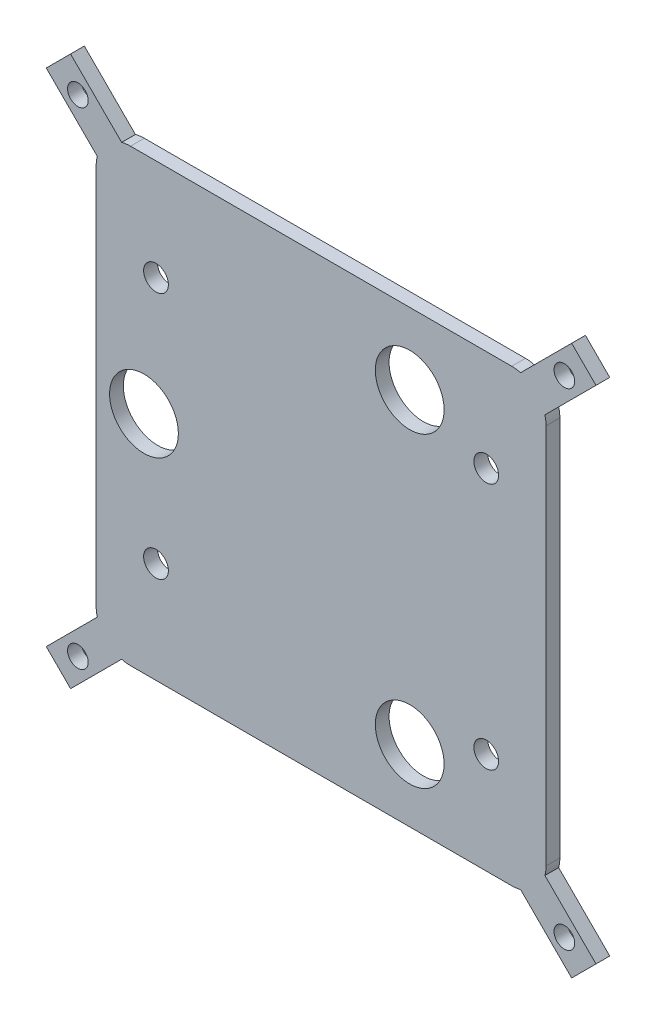
SolidWorks part; units mm, degrees
ref_plane "前视基准面" through (0, 0, 0) normal (0, 0, 1) x (1, 0, 0)
ref_plane "上视基准面" through (0, 0, 0) normal (0, 1, 0) x (1, 0, 0)
ref_plane "右视基准面" through (0, 0, 0) normal (1, 0, 0) x (0, 0, -1)
other "Configuration Table"
sketch "草图1" plane through (0, 0, 0) normal (0, 0, 1) x (1, 0, 0)
  line L0 (-24, 18) -> (24, 18) construction
  line L1 (24, 18) -> (24, -18) construction
  line L2 (24, -18) -> (-24, -18) construction
  line L3 (-24, -18) -> (-24, 18) construction
  line L4 (-24, 18) -> (24, -18) construction
  line L5 (24, 18) -> (-24, -18) construction
  line L6 (-27.7, -32.7) -> (27.7, -32.7)
  line L7 (-32.7, -27.7) -> (-32.7, 27.7)
  line L8 (-27.7, 32.7) -> (27.7, 32.7)
  line L9 (32.7, -27.7) -> (32.7, 27.7)
  line L10 (-32.7, -32.7) -> (32.7, 32.7) construction
  line L11 (-32.7, 32.7) -> (32.7, -32.7) construction
  circle A0 centre (24, 18) radius 1.8
  circle A1 centre (-24, 18) radius 1.8
  circle A2 centre (-24, -18) radius 1.8
  circle A3 centre (24, -18) radius 1.8
  arc A4 (-32.7, -27.7) -> (-27.7, -32.7) centre (-27.7, -27.7) ccw
  arc A5 (27.7, -32.7) -> (32.7, -27.7) centre (27.7, -27.7) ccw
  arc A6 (32.7, 27.7) -> (27.7, 32.7) centre (27.7, 27.7) ccw
  arc A7 (-32.7, 27.7) -> (-27.7, 32.7) centre (-27.7, 27.7) cw
  point P8 (0, 0)
  point P9 (0, 0)
  dimension "D3" = 3.6
  dimension "D4" = 3.6
  dimension "D5" = 3.6
  dimension "D6" = 3.6
  dimension "D8" = 5
  dimension "D1" = 48
  dimension "D2" = 36
  dimension "D7" = 65.4
extrude "凸台-拉伸1" add sketch "草图1" along normal blind 2
sketch "草图3" plane through (0, 0, 2) normal (0, 0, 1) x (1, 0, 0)
  line L0 (0, 0) -> (-31.2355, 31.2355) construction
  line L17 (-33.0033, 29.4678) -> (-29.4678, 33.0033) construction
  line L18 (-33.0033, 29.4678) -> (-39.9515, 36.416)
  line L19 (-29.4678, 33.0033) -> (-36.416, 39.9515)
  line L20 (-27.7, -32.7) -> (27.7, -32.7)
  line L21 (32.7, -27.7) -> (32.7, 27.7)
  line L22 (27.7, 32.7) -> (-27.7, 32.7)
  line L23 (-32.7, 27.7) -> (-32.7, -27.7)
  line L24 (-27.7, -32.7) -> (27.7, -32.7)
  line L25 (32.7, -27.7) -> (32.7, 27.7)
  line L26 (27.7, 32.7) -> (-27.7, 32.7)
  line L27 (-32.7, 27.7) -> (-32.7, -27.7)
  line L28 (-39.9515, 36.416) -> (-36.416, 39.9515)
  line L29 (-29.4678, 33.0033) -> (-33.0033, 29.4678) construction
  line L30 (-29.4678, 33.0033) -> (-27.5018, 31.0373)
  line L31 (-33.0033, 29.4678) -> (-31.0373, 27.5018)
  line L32 (-27.5018, 31.0373) -> (-31.0373, 27.5018)
  line L33 (0, 0) -> (-38.1838, 38.1838) construction
  line L34 (29.4678, 33.0033) -> (36.416, 39.9515)
  line L35 (33.0033, 29.4678) -> (39.9515, 36.416)
  line L36 (36.416, 39.9515) -> (39.9515, 36.416)
  line L37 (33.0033, 29.4678) -> (31.0373, 27.5018)
  line L38 (29.4678, 33.0033) -> (27.5018, 31.0373)
  line L39 (31.0373, 27.5018) -> (27.5018, 31.0373)
  line L40 (29.4678, 33.0033) -> (33.0033, 29.4678) construction
  line L41 (33.0033, 29.4678) -> (29.4678, 33.0033) construction
  line L42 (33.0033, -29.4678) -> (39.9515, -36.416)
  line L43 (29.4678, -33.0033) -> (36.416, -39.9515)
  line L44 (39.9515, -36.416) -> (36.416, -39.9515)
  line L45 (29.4678, -33.0033) -> (27.5018, -31.0373)
  line L46 (33.0033, -29.4678) -> (31.0373, -27.5018)
  line L47 (27.5018, -31.0373) -> (31.0373, -27.5018)
  line L48 (33.0033, -29.4678) -> (29.4678, -33.0033) construction
  line L49 (29.4678, -33.0033) -> (33.0033, -29.4678) construction
  line L50 (-29.4678, -33.0033) -> (-36.416, -39.9515)
  line L51 (-33.0033, -29.4678) -> (-39.9515, -36.416)
  line L52 (-36.416, -39.9515) -> (-39.9515, -36.416)
  line L53 (-33.0033, -29.4678) -> (-31.0373, -27.5018)
  line L54 (-29.4678, -33.0033) -> (-27.5018, -31.0373)
  line L55 (-31.0373, -27.5018) -> (-27.5018, -31.0373)
  line L56 (-29.4678, -33.0033) -> (-33.0033, -29.4678) construction
  line L57 (-33.0033, -29.4678) -> (-29.4678, -33.0033) construction
  arc A4 (-32.7, -27.7) -> (-27.7, -32.7) centre (-27.7, -27.7) ccw
  arc A5 (27.7, -32.7) -> (32.7, -27.7) centre (27.7, -27.7) ccw
  arc A6 (32.7, 27.7) -> (27.7, 32.7) centre (27.7, 27.7) ccw
  arc A7 (-27.7, 32.7) -> (-32.7, 27.7) centre (-27.7, 27.7) ccw
  arc A8 (-32.7, -27.7) -> (-27.7, -32.7) centre (-27.7, -27.7) ccw construction
  arc A9 (27.7, -32.7) -> (32.7, -27.7) centre (27.7, -27.7) ccw construction
  arc A10 (32.7, 27.7) -> (27.7, 32.7) centre (27.7, 27.7) ccw construction
  arc A11 (-27.7, 32.7) -> (-32.7, 27.7) centre (-27.7, 27.7) ccw construction
  point P10 (-31.2355, 31.2355)
  point P43 (0, 0)
  arc M48 (-32.7, -27.7) -> (-27.7, -32.7) centre (-27.7, -27.7) ccw
  arc M50 (27.7, -32.7) -> (32.7, -27.7) centre (27.7, -27.7) ccw
  arc M52 (32.7, 27.7) -> (27.7, 32.7) centre (27.7, 27.7) ccw
  arc M54 (-27.7, 32.7) -> (-32.7, 27.7) centre (-27.7, 27.7) ccw
  dimension "D2" = 54
  dimension "D3" = 5
  dimension "D1" = 0
  dimension "D4" = 4
extrude "凸台-拉伸2" add sketch "草图3" against normal up to surface (2 mm away) contours L18 L31 L30 L19 L28 M54 | L32 L30 L31 M54 | L39 L37 L38 M52 | L34 L38 L37 L35 L36 M52 | L47 L45 L46 M50 | L42 L46 L45 L43 L44 M50 | L50 L54 L53 L51 L52 M48 | L55 L53 L54 M48 up to face at (0, 0, 0)
sketch "草图4" plane through (0, 0, 2) normal (0, 0, 1) x (1, 0, 0)
  line L0 (0, 0) -> (-38.1838, 38.1838) construction
  line L16 (-32.5296, -28.9941) -> (-39.9515, -36.416)
  line L17 (-39.9515, -36.416) -> (-36.416, -39.9515)
  line L18 (-36.416, -39.9515) -> (-28.9941, -32.5296)
  line L19 (-27.7, -32.7) -> (27.7, -32.7)
  line L20 (28.9941, -32.5296) -> (36.416, -39.9515)
  line L21 (36.416, -39.9515) -> (39.9515, -36.416)
  line L22 (39.9515, -36.416) -> (32.5296, -28.9941)
  line L23 (32.7, -27.7) -> (32.7, 27.7)
  line L24 (32.5296, 28.9941) -> (39.9515, 36.416)
  line L25 (39.9515, 36.416) -> (36.416, 39.9515)
  line L26 (36.416, 39.9515) -> (28.9941, 32.5296)
  line L27 (27.7, 32.7) -> (-27.7, 32.7)
  line L28 (-28.9941, 32.5296) -> (-36.416, 39.9515)
  line L29 (-36.416, 39.9515) -> (-39.9515, 36.416)
  line L30 (-39.9515, 36.416) -> (-32.5296, 28.9941)
  line L31 (-32.7, 27.7) -> (-32.7, -27.7)
  line L32 (-32.5296, -28.9941) -> (-39.9515, -36.416)
  line L33 (-39.9515, -36.416) -> (-36.416, -39.9515)
  line L34 (-36.416, -39.9515) -> (-28.9941, -32.5296)
  line L35 (-27.7, -32.7) -> (27.7, -32.7)
  line L36 (28.9941, -32.5296) -> (36.416, -39.9515)
  line L37 (36.416, -39.9515) -> (39.9515, -36.416)
  line L38 (39.9515, -36.416) -> (32.5296, -28.9941)
  line L39 (32.7, -27.7) -> (32.7, 27.7)
  line L40 (32.5296, 28.9941) -> (39.9515, 36.416)
  line L41 (39.9515, 36.416) -> (36.416, 39.9515)
  line L42 (36.416, 39.9515) -> (28.9941, 32.5296)
  line L43 (27.7, 32.7) -> (-27.7, 32.7)
  line L44 (-28.9941, 32.5296) -> (-36.416, 39.9515)
  line L45 (-36.416, 39.9515) -> (-39.9515, 36.416)
  line L46 (-39.9515, 36.416) -> (-32.5296, 28.9941)
  line L47 (-32.7, 27.7) -> (-32.7, -27.7)
  circle A0 centre (-35.3553, 35.3553) radius 1.5
  circle A1 centre (35.3553, 35.3553) radius 1.5
  circle A2 centre (35.3553, -35.3553) radius 1.5
  circle A3 centre (-35.3553, -35.3553) radius 1.5
  arc A8 (-32.7, -27.7) -> (-32.5296, -28.9941) centre (-27.7, -27.7) ccw
  arc A9 (-28.9941, -32.5296) -> (-27.7, -32.7) centre (-27.7, -27.7) ccw
  arc A10 (27.7, -32.7) -> (28.9941, -32.5296) centre (27.7, -27.7) ccw
  arc A11 (32.5296, -28.9941) -> (32.7, -27.7) centre (27.7, -27.7) ccw
  arc A12 (32.7, 27.7) -> (32.5296, 28.9941) centre (27.7, 27.7) ccw
  arc A13 (28.9941, 32.5296) -> (27.7, 32.7) centre (27.7, 27.7) ccw
  arc A14 (-27.7, 32.7) -> (-28.9941, 32.5296) centre (-27.7, 27.7) ccw
  arc A15 (-32.5296, 28.9941) -> (-32.7, 27.7) centre (-27.7, 27.7) ccw
  arc A16 (-32.7, -27.7) -> (-32.5296, -28.9941) centre (-27.7, -27.7) ccw
  arc A17 (-28.9941, -32.5296) -> (-27.7, -32.7) centre (-27.7, -27.7) ccw
  arc A18 (27.7, -32.7) -> (28.9941, -32.5296) centre (27.7, -27.7) ccw
  arc A19 (32.5296, -28.9941) -> (32.7, -27.7) centre (27.7, -27.7) ccw
  arc A20 (32.7, 27.7) -> (32.5296, 28.9941) centre (27.7, 27.7) ccw
  arc A21 (28.9941, 32.5296) -> (27.7, 32.7) centre (27.7, 27.7) ccw
  arc A22 (-27.7, 32.7) -> (-28.9941, 32.5296) centre (-27.7, 27.7) ccw
  arc A23 (-32.5296, 28.9941) -> (-32.7, 27.7) centre (-27.7, 27.7) ccw
  point P38 (0, 0)
  dimension "D2" = 3
  dimension "D3" = 50
  dimension "D1" = 0
  dimension "D4" = 4
extrude "切除-拉伸1" cut sketch "草图4" against normal up to next contours A0 | A1 | A2 | A3
sketch "草图5" plane through (0, 0, 2) normal (0, 0, 1) x (1, 0, 0)
  line L2 (-29, 0) -> (-22.5, 0) construction
  line L7 (0, 0) -> (-50000, 0) construction
  circle A2 centre (0, 0) radius 22.5 construction
  circle A3 centre (0, 0) radius 29 construction
  circle A8 centre (-25.75, 0) radius 5
  circle A9 centre (0, 0) radius 22.5 construction
  circle A10 centre (0, 0) radius 29 construction
  circle A11 centre (12.875, 22.3002) radius 5
  circle A12 centre (12.875, -22.3002) radius 5
  point P9 (-25.75, 0)
  point P14 (0, 0)
  point P20 (22.0587, -28.5564)
  point P25 (22.0587, -28.5564)
  dimension "D1" = 45
  dimension "D2" = 58
  dimension "D5" = 10
  dimension "D3" = 25.75
  dimension "D4" = 3
  dimension "D6" = 0
extrude "切除-拉伸2" cut sketch "草图5" against normal up to next
